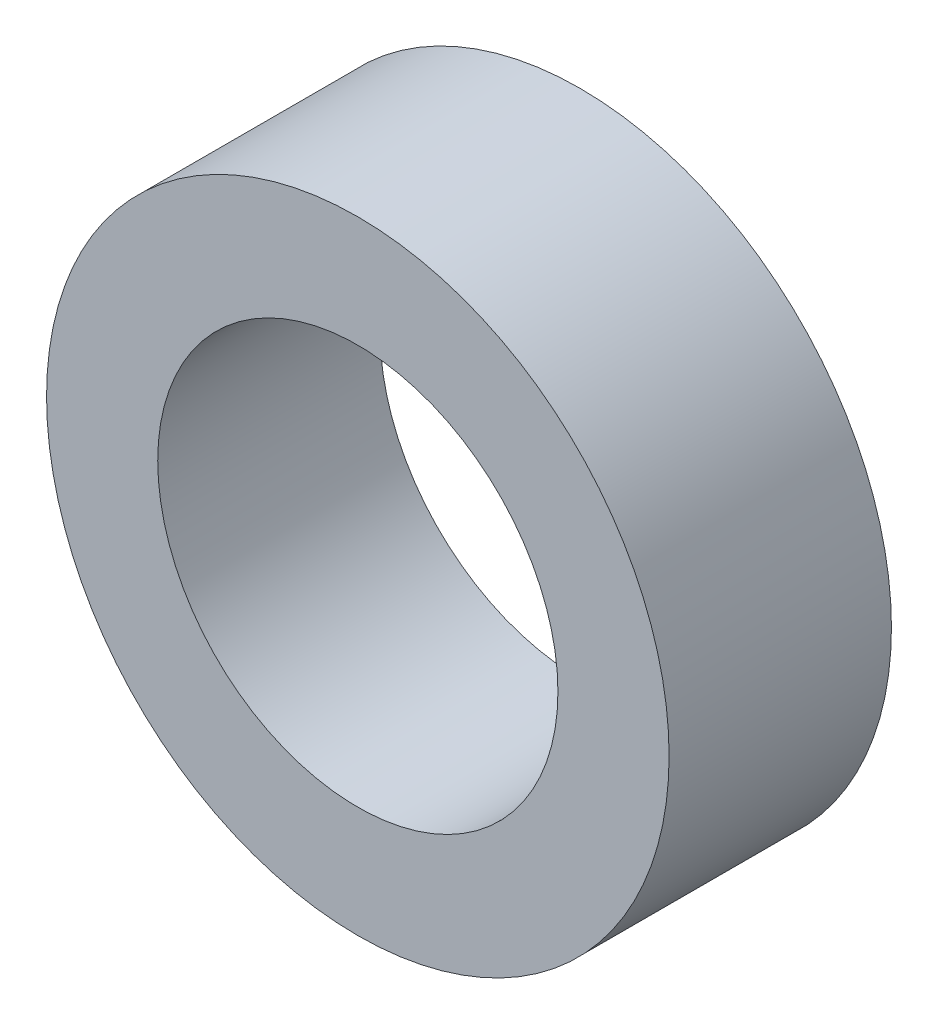
SolidWorks part; units mm, degrees
ref_plane "前视基准面" through (0, 0, 0) normal (0, 0, 1) x (1, 0, 0)
ref_plane "上视基准面" through (0, 0, 0) normal (0, 1, 0) x (1, 0, 0)
ref_plane "右视基准面" through (0, 0, 0) normal (1, 0, 0) x (0, 0, -1)
other "Configuration Table"
sketch "草图1" plane through (0, 0, 0) normal (0, 0, 1) x (1, 0, 0)
  circle A0 centre (0, 0) radius 2.25
  circle A1 centre (0, 0) radius 3.5
  dimension "D1" = 4.5
  dimension "D2" = 7
extrude "凸台-拉伸1" add sketch "草图1" along normal blind 2.5
